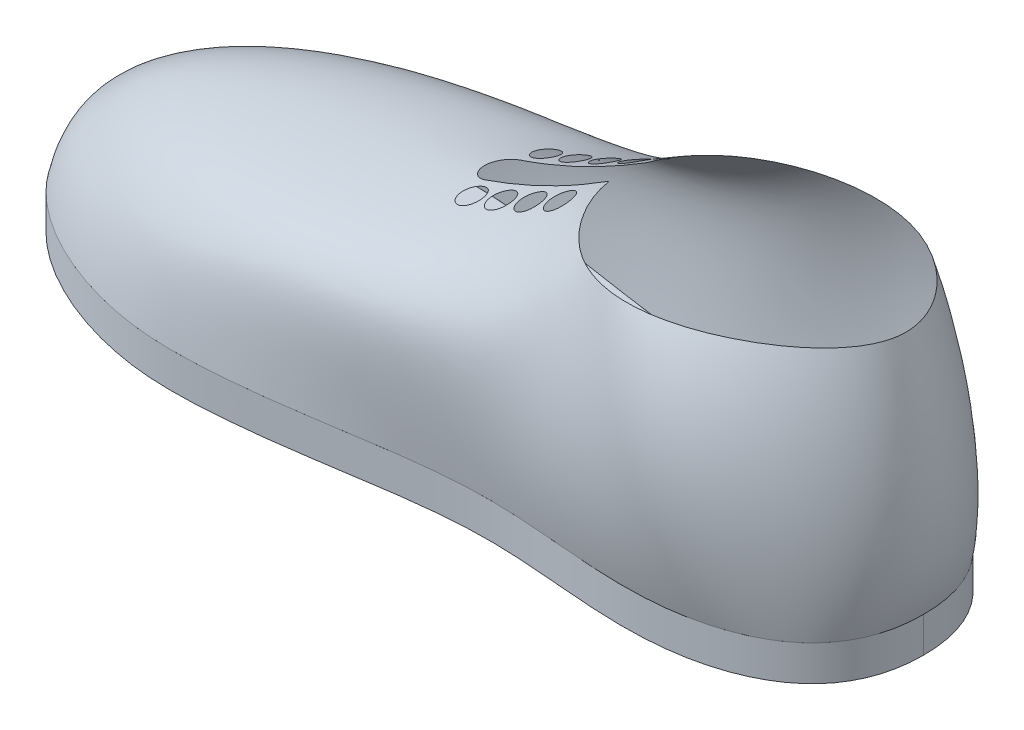
SolidWorks part; units mm, degrees
ref_plane "Front Plane" through (0, 0, 0) normal (0, 0, 1) x (1, 0, 0)
ref_plane "Top Plane" through (0, 0, 0) normal (0, 1, 0) x (1, 0, 0)
ref_plane "Right Plane" through (0, 0, 0) normal (1, 0, 0) x (0, 0, -1)
sketch "Sketch1" plane through (0, 0, 0) normal (0, 1, 0) x (1, 0, 0)
  line L0 (35, 0) -> (-250, 0) construction
  line L1 (0, 0) -> (0, 40) construction
  line L2 (-70, 0) -> (-70, 40) construction
  line L3 (-170, 0) -> (-170, 50)
  line L4 (-170, 79.8626) -> (-170, 50) construction
  line L5 (35, -19.7987) -> (35, 19.7987) construction
  line L6 (-250, 36.0833) -> (-250, -36.0833) construction
  line L7 (-138.9495, 50) -> (-198.9415, 50) construction
  spline S0 degree 3 poles (-250, 0) (-250, 25.5443) (-206.069, 51.03) (-130.9725, 49.2159) (-78.7315, 33.3591) (-5.0092, 49.9046) (35, 24.7484) (35, 0) knots 0 0 0 0 0.267008 0.328281 0.612721 0.832854 1 1 1 1
  spline S1 degree 3 poles (-250, 0) (-250, -25.5443) (-206.069, -51.03) (-130.9725, -49.2159) (-78.7315, -33.3591) (-5.0092, -49.9046) (35, -24.7484) (35, 0) knots 0 0 0 0 0.267008 0.328281 0.612721 0.832854 1 1 1 1
  dimension "D1" = 285
  dimension "D2" = 35
  dimension "D3" = 40
  dimension "D4" = 40
  dimension "D5" = 50
  dimension "D6" = 80
  dimension "D7" = 70
extrude "Boss-Extrude1" add sketch "Sketch1" along normal blind 12 contours S1 S0
ref_plane "Plane1" through (0, 92, 0) normal (0, 1, 0) x (1, 0, 0)
sketch "Sketch2" plane through (0, 92, 0) normal (0, 1, 0) x (1, 0, 0)
  line L0 (29, 0) -> (-66, 0) construction
  line L1 (0, 32) -> (0, -32) construction
  line L2 (29, 10.3704) -> (29, -10.377) construction
  spline S0 degree 3 poles (27.7124, -14.1651) (30.2876, 11.5717) (-5.7452, 50.6226) (-82.2167, 15.295) (-49.0927, -42.9842) (-2.6678, -38.7527) (27.7124, -14.1651) (30.2876, 11.5717) (-5.7452, 50.6226) knots -0.377482 -0.176165 -0.017617 0 0.176165 0.475372 0.622518 0.823835 0.982383 1 1.176165 1.475372 1.622518 only from (29, 0) to (29, 0)
  dimension "D1" = 95
  dimension "D2" = 29
  dimension "D3" = 32
  dimension "D4" = 32
sketch "Sketch3" plane through (0, 0, 0) normal (0, 0, 1) x (1, 0, 0)
  spline S0 degree 3 poles (29, 92) (38.2506, 65.2017) (43.7685, 35.4515) (35, 12) knots 0 0 0 0 1 1 1 1
  point P2 (0, 0)
  point P3 (0, 0)
  point P4 (0, 0)
  point P8 (0, 0)
sketch "Sketch5" plane through (0, 0, 0) normal (0, 0, 1) x (1, 0, 0)
  spline S0 degree 3 poles (-66, 92) (-106.6252, 66.7379) (-155.0557, 62.1845) (-242.1467, 47.03) (-250, 12) knots 0 0 0 0 0.549033 1 1 1 1
  point P2 (0, 0)
  point P4 (0, 0)
  point P9 (0, 0)
  point P11 (0, 0)
  point P12 (0, 0)
  point P13 (0, 0)
sketch3d "3DSketch1"
  spline S0 degree 3 poles (-24.4621, 92, 38.6265) (-11.3097, 65.4055, 50.2543) (-16.454, 37.7698, 50.1264) (-9.8492, 12, 41.8163) knots 0 0 0 0 1 1 1 1
  spline S1 degree 3 poles (27.7124, 92, 14.1651) (30.2876, 92, -11.5717) (-5.7452, 92, -50.6226) (-82.2167, 92, -15.295) (-49.0927, 92, 42.9842) (-2.6678, 92, 38.7527) (27.7124, 92, 14.1651) (30.2876, 92, -11.5717) (-5.7452, 92, -50.6226) knots -0.377482 -0.176165 -0.017617 0 0.176165 0.475372 0.622518 0.823835 0.982383 1 1.176165 1.475372 1.622518 only from (29, 92, 0) to (29, 92, 0) construction
  spline S2 degree 3 poles (-250, 12, 0) (-250, 12, 25.5443) (-206.069, 12, 51.03) (-130.9725, 12, 49.2159) (-78.7315, 12, 33.3591) (-5.0092, 12, 49.9046) (35, 12, 24.7484) (35, 12, 0) knots 0 0 0 0 0.267008 0.328281 0.612721 0.832854 1 1 1 1 construction
  point P2 (-24.4621, 92, 38.6265)
  point P3 (0, 0, 0)
  point P7 (0, 0, 0)
  point P8 (0, 0, 0)
sketch3d "3DSketch2"
  spline S0 degree 2 poles (-11.9431, 92, -34.1698) (-21.9538, 61.0214, -46.9504) (-31.7374, 12, -42.4878) knots 0 0 0 1 1 1
  spline S1 degree 3 poles (27.7124, 92, 14.1651) (30.2876, 92, -11.5717) (-5.7452, 92, -50.6226) (-82.2167, 92, -15.295) (-49.0927, 92, 42.9842) (-2.6678, 92, 38.7527) (27.7124, 92, 14.1651) (30.2876, 92, -11.5717) (-5.7452, 92, -50.6226) knots -0.377482 -0.176165 -0.017617 0 0.176165 0.475372 0.622518 0.823835 0.982383 1 1.176165 1.475372 1.622518 only from (29, 92, 0) to (29, 92, 0) construction
  spline S2 degree 3 poles (-250, 12, 0) (-250, 12, -25.5443) (-206.069, 12, -51.03) (-130.9725, 12, -49.2159) (-78.7315, 12, -33.3591) (-5.0092, 12, -49.9046) (35, 12, -24.7484) (35, 12, 0) knots 0 0 0 0 0.267008 0.328281 0.612721 0.832854 1 1 1 1 construction
surface "Surface-Loft1"
sketch "Sketch6" plane through (0, 92, 0) normal (0, 1, 0) x (1, 0, 0)
  line L0 (-58, 0) -> (0, 0) construction
  line L1 (-58, 6) -> (-108, 6)
  line L2 (-58, 6) -> (-58, -6)
  line L3 (-58, -6) -> (-108, -6)
  line L4 (-108, 6) -> (-108, -6) construction
  line L5 (-58, 12.6166) -> (-118, 12.6166) construction
  line L6 (-58, -12.6166) -> (-118, -12.6166) construction
  circle A0 centre (-75.8574, 12.6166) radius 4
  circle A1 centre (-88, 12.6166) radius 0.2042
  circle A2 centre (-85.8574, 12.6166) radius 4
  circle A3 centre (-95.8574, 12.6166) radius 4.0108
  circle A4 centre (-105.8574, 12.6166) radius 4
  arc A5 (-108, 6) -> (-108, -6) centre (-108, 0) ccw
  circle A6 centre (-105.8574, -12.6166) radius 4
  circle A7 centre (-95.8574, -12.6166) radius 4.0108
  circle A8 centre (-85.8574, -12.6166) radius 4
  circle A9 centre (-75.8574, -12.6166) radius 4
  dimension "D4" = 10
  dimension "D1" = 12
  dimension "D2" = 50
  dimension "D3" = 58
  dimension "D5" = 10
  dimension "D6" = 22.1426
  dimension "D7" = 10
surface "Surface-Trim1"
